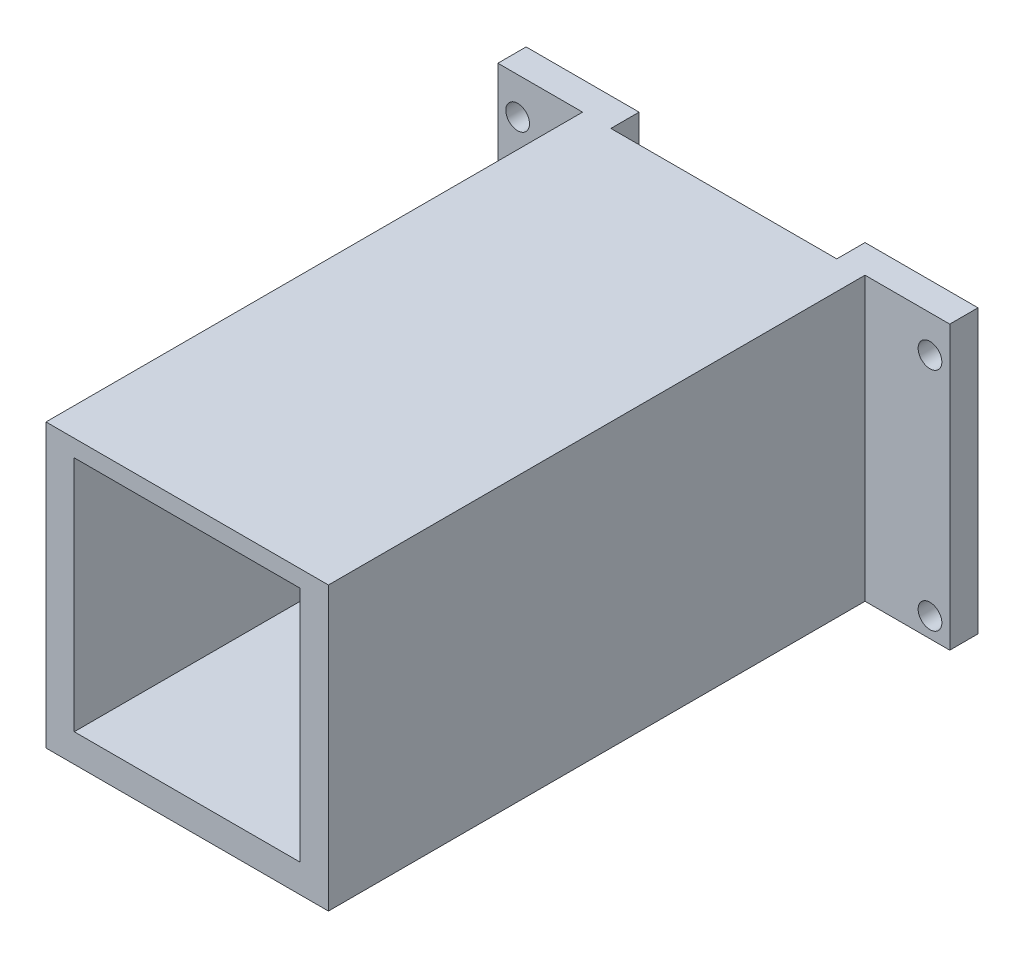
SolidWorks part; units mm, degrees
ref_plane "前基準面" through (0, 0, 0) normal (0, 0, 1) x (1, 0, 0)
ref_plane "上基準面" through (0, 0, 0) normal (0, 1, 0) x (1, 0, 0)
ref_plane "右基準面" through (0, 0, 0) normal (1, 0, 0) x (0, 0, -1)
sketch "草圖1" plane through (0, 0, 0) normal (0, 0, 1) x (1, 0, 0)
  line L1 (0, 0) -> (80, 0)
  line L2 (0, 0) -> (0, 50)
  line L3 (0, 50) -> (80, 50)
  line L4 (80, 0) -> (80, 50)
  point P4 (0, 0)
extrude "填料-伸長1" add sketch "草圖1" along normal blind 5
sketch "草圖2" plane through (0, 0, 0) normal (0, 0, 1) x (1, 0, 0)
  line L0 (80, 50) -> (0, 50) construction
  line L1 (15, 0) -> (65, 0)
  line L2 (15, 0) -> (15, 50)
  line L3 (15, 50) -> (65, 50)
  line L4 (65, 0) -> (65, 50)
extrude "填料-伸長2" add sketch "草圖2" along normal blind 100
sketch "草圖4" plane through (0, 0, 0) normal (0, 0, 1) x (1, 0, 0)
  line L1 (20, 5) -> (60, 5)
  line L2 (20, 5) -> (20, 47)
  line L3 (20, 47) -> (60, 47)
  line L4 (60, 5) -> (60, 47)
  point P4 (0, 0)
extrude "除料-伸長1" cut sketch "草圖4" along normal through all
sketch "草圖5" plane through (0, 0, 0) normal (0, 0, 1) x (1, 0, 0)
  circle A0 centre (76.5, 3.5) radius 2.1
  circle A1 centre (76.5, 43.5) radius 2.1
  circle A2 centre (3.5, 3.5) radius 2.1
  circle A3 centre (3.5, 43.5) radius 2.1
  point P8 (0, 0)
  point P9 (0, 0)
  point P10 (0, 0)
  point P11 (0, 0)
  point P12 (0, 0)
  point P13 (0, 0)
extrude "除料-伸長2" cut sketch "草圖5" along normal blind 10
sketch "草圖7" plane through (0, 0, 0) normal (0, 1, 0) x (1, 0, 0)
  line L0 (0, 0) -> (80, 0) construction
  line L1 (60, 0) -> (20, 0)
  line L2 (60, 0) -> (60, -5)
  line L3 (60, -5) -> (20, -5)
  line L4 (20, 0) -> (20, -5)
  point P6 (0, 0)
  point P7 (0, 0)
  point P8 (0, 0)
  point P9 (0, 0)
extrude "除料-伸長4" cut sketch "草圖7" along normal through all from offset 40
